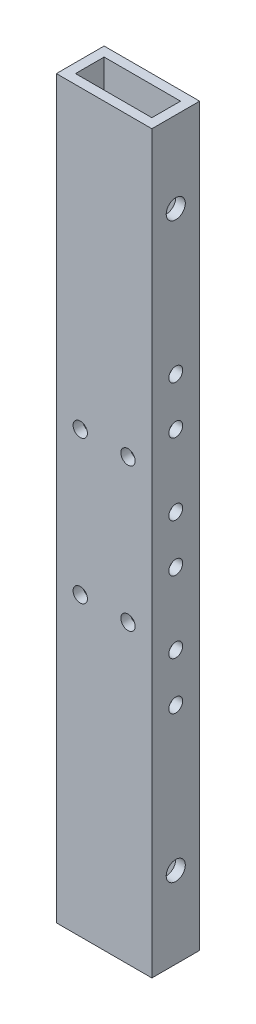
SolidWorks part; units mm, degrees
ref_plane "前视基准面" through (0, 0, 0) normal (0, 0, 1) x (1, 0, 0)
ref_plane "上视基准面" through (0, 0, 0) normal (0, 1, 0) x (1, 0, 0)
ref_plane "右视基准面" through (0, 0, 0) normal (1, 0, 0) x (0, 0, -1)
sketch "草图1" plane through (0, 0, 0) normal (0, 1, 0) x (1, 0, 0)
  line L1 (-10, 5) -> (10, 5)
  line L2 (-10, 5) -> (-10, -5)
  line L3 (-10, -5) -> (10, -5)
  line L4 (10, 5) -> (10, -5)
  line L5 (-10, 5) -> (10, -5) construction
  line L6 (-10, -5) -> (10, 5) construction
  line L7 (-8, 3) -> (8, 3)
  line L8 (-8, 3) -> (-8, -3)
  line L9 (-8, -3) -> (8, -3)
  line L10 (8, 3) -> (8, -3)
  line L11 (-8, 3) -> (8, -3) construction
  line L12 (-8, -3) -> (8, 3) construction
  point P0 (0, 0)
  point P6 (0, 0)
  dimension "D1" = 10
  dimension "D2" = 20
  dimension "D3" = 2
  dimension "D4" = 2
extrude "凸台-拉伸1" add sketch "草图1" along normal mid plane 154
sketch "草图2" plane through (10, 0, 0) normal (1, 0, 0) x (0, 0, -1)
  line L0 (0, 0) -> (0, -17.282) construction
  line L1 (0, 0) -> (-14.5337, 0) construction
  circle A0 centre (0, 5) radius 1.45
  circle A1 centre (0, 20) radius 1.45
  circle A2 centre (0, 30) radius 1.45
  circle A3 centre (0, -30) radius 1.45
  circle A4 centre (0, -20) radius 1.45
  circle A5 centre (0, -5) radius 1.45
  circle A6 centre (0, 60) radius 2
  circle A7 centre (0, -60) radius 2
  dimension "D4" = 2.9
  dimension "D5" = 4
  dimension "D1" = 5
  dimension "D2" = 10
  dimension "D3" = 15
  dimension "D6" = 30
extrude "切除-拉伸1" cut sketch "草图2" against normal through all
sketch "草图3" plane through (0, 0, -5) normal (0, 0, -1) x (-1, 0, 0)
  line L0 (265.7, -20) -> (-54.3, -20) construction
  line L1 (10, 77) -> (10, -77) construction
  line L2 (0, 0) -> (17.2852, 0) construction
  line L3 (5, -15) -> (-5, -15) construction
  circle A0 centre (5, -15) radius 1.5
  circle A1 centre (-5, -15) radius 1.5
  circle A2 centre (5, 15) radius 1.5
  circle A3 centre (-5, 15) radius 1.5
  dimension "D4" = 3
  dimension "D1" = 5
  dimension "D2" = 5
  dimension "D3" = 10
extrude "切除-拉伸2" cut sketch "草图3" against normal through all
